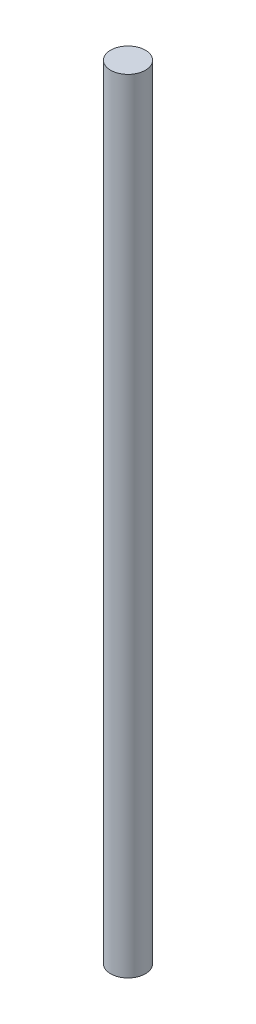
SolidWorks part; units mm, degrees
ref_plane "Front Plane" through (0, 0, 0) normal (0, 0, 1) x (1, 0, 0)
ref_plane "Top Plane" through (0, 0, 0) normal (0, 1, 0) x (1, 0, 0)
ref_plane "Right Plane" through (0, 0, 0) normal (1, 0, 0) x (0, 0, -1)
sketch "Sketch1" plane through (0, 0, 0) normal (0, 1, 0) x (1, 0, 0)
  circle A0 centre (0, 0) radius 2
  dimension "D1" = 4
extrude "Boss-Extrude1" add sketch "Sketch1" along normal mid plane 90
